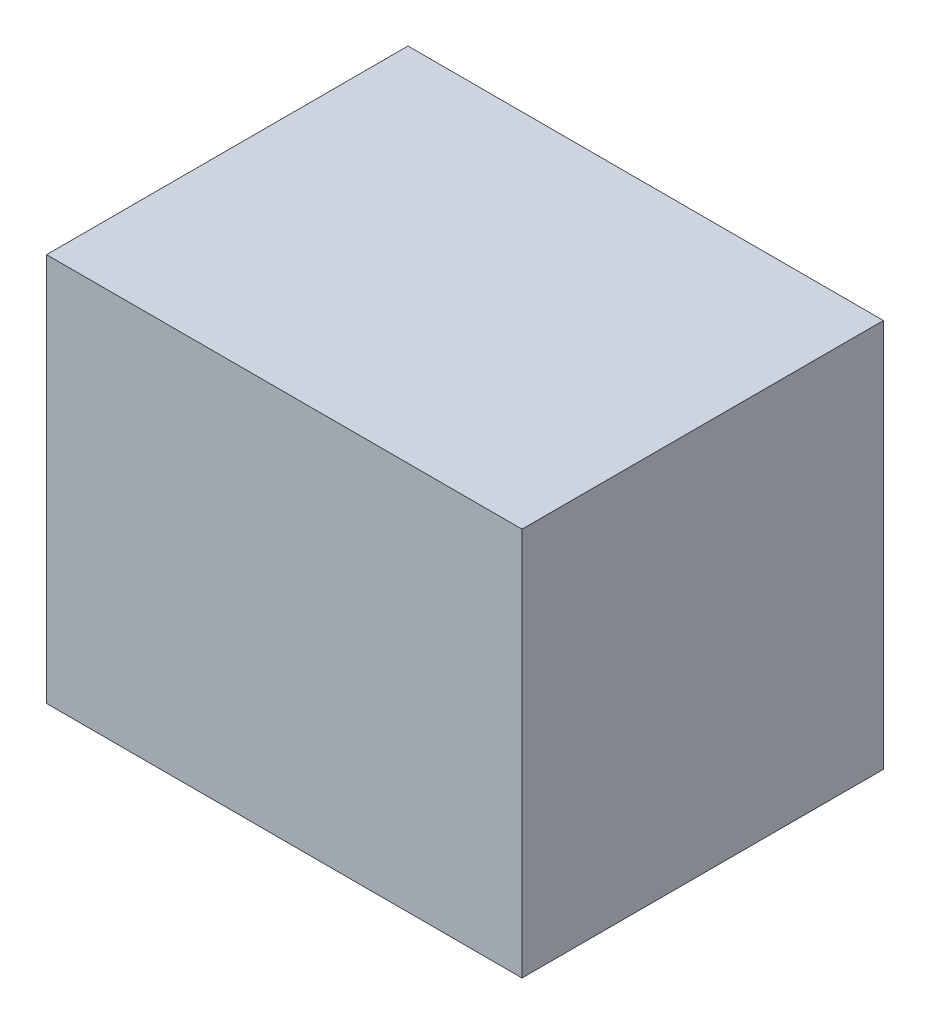
SolidWorks part; units mm, degrees
ref_plane "Front Plane" through (0, 0, 0) normal (0, 0, 1) x (1, 0, 0)
ref_plane "Top Plane" through (0, 0, 0) normal (0, 1, 0) x (1, 0, 0)
ref_plane "Right Plane" through (0, 0, 0) normal (1, 0, 0) x (0, 0, -1)
sketch "Sketch1" plane through (0, 0, 0) normal (0, 1, 0) x (1, 0, 0)
  line L0 (214.2877, 69.0976) -> (214.2877, -155.9024) construction
  line L1 (-81.7123, 69.0976) -> (214.2877, 69.0976)
  line L2 (-81.7123, 69.0976) -> (-81.7123, -155.9024)
  line L3 (-81.7123, -155.9024) -> (214.2877, -155.9024)
  line L4 (214.2877, 69.0976) -> (214.2877, -155.9024)
  line L5 (-81.7123, 69.0976) -> (214.2877, -155.9024) construction
  line L6 (-81.7123, -155.9024) -> (214.2877, 69.0976) construction
  point P0 (0, 0)
  point P6 (0, 0)
  point P7 (0, 0)
  point P8 (0, 0)
  point P9 (0, 0)
  point P10 (213.7128, -153.5569)
  point P11 (214.2877, -155.9024)
extrude "Boss-Extrude1" add sketch "Sketch1" along normal blind 242
